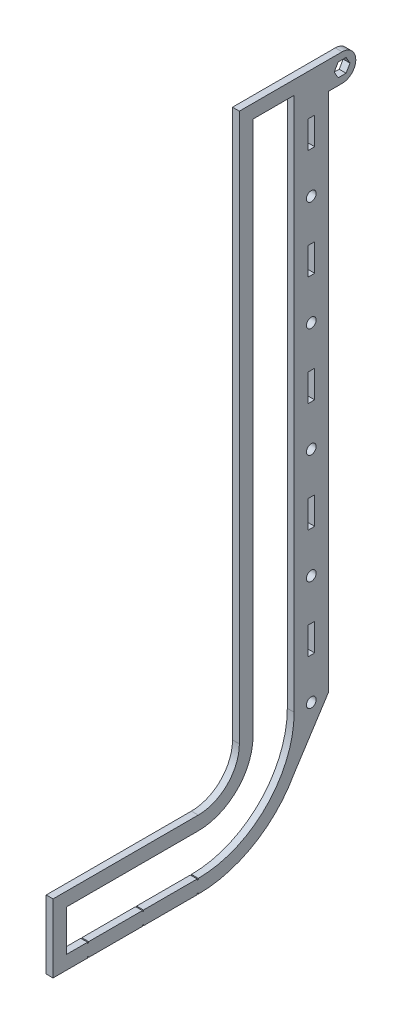
SolidWorks part; units mm, degrees
ref_plane "Front Plane" through (0, 0, 0) normal (0, 0, 1) x (1, 0, 0)
ref_plane "Top Plane" through (0, 0, 0) normal (0, 1, 0) x (1, 0, 0)
ref_plane "Right Plane" through (0, 0, 0) normal (1, 0, 0) x (0, 0, -1)
sketch "Sketch2" plane through (0, 0, 0) normal (1, 0, 0) x (0, 0, -1)
  line L0 (-44.958, -44.45) -> (-69.85, -44.45)
  line L1 (15.875, 254) -> (22.225, 254)
  line L2 (0, 0) -> (0, 247.65)
  line L3 (0, 254) -> (15.875, 254)
  line L4 (15.875, 0) -> (15.875, 241.3)
  line L6 (-44.958, -50.8) -> (-69.85, -50.8)
  line L7 (-111.76, -50.8) -> (-111.76, -44.45)
  line L8 (-105.41, -44.45) -> (-95.758, -44.45)
  line L9 (-44.45, -44.45) -> (-44.45, -44.958)
  line L10 (0, 254) -> (-25.4, 254)
  line L11 (-44.45, -44.958) -> (-44.958, -44.958)
  line L12 (0, 247.65) -> (-19.05, 247.65)
  line L13 (-25.4, 254) -> (-25.4, 247.65)
  line L14 (-44.958, -44.45) -> (-44.958, -44.958)
  line L15 (-25.4, 247.65) -> (-25.4, 0)
  line L16 (15.875, 241.3) -> (22.225, 241.3)
  line L17 (-19.05, 247.65) -> (-19.05, 0)
  line L18 (-44.45, -19.05) -> (-111.76, -19.05)
  line L19 (-44.45, -50.8) -> (-44.45, -50.292)
  line L20 (-44.45, -25.4) -> (-105.41, -25.4)
  line L21 (-111.76, -19.05) -> (-111.76, -25.4)
  line L22 (-44.45, -50.292) -> (-44.958, -50.292)
  line L23 (-111.76, -25.4) -> (-111.76, -44.45)
  line L24 (-44.958, -50.8) -> (-44.958, -50.292)
  line L25 (-105.41, -25.4) -> (-105.41, -44.45)
  line L26 (-70.358, -44.45) -> (-95.25, -44.45)
  line L27 (6.35, 222.25) -> (9.525, 222.25)
  line L28 (6.35, 222.25) -> (6.35, 234.95)
  line L29 (6.35, 234.95) -> (9.525, 234.95)
  line L30 (9.525, 234.95) -> (9.525, 222.25)
  line L31 (15.875, 0) -> (0, -24.5934)
  line L32 (-70.358, -50.8) -> (-95.25, -50.8)
  line L33 (-69.85, -44.45) -> (-69.85, -44.958)
  line L34 (-69.85, -44.958) -> (-70.358, -44.958)
  line L35 (9.525, 171.45) -> (9.525, 184.15)
  line L36 (6.35, 171.45) -> (9.525, 171.45)
  line L37 (6.35, 184.15) -> (6.35, 171.45)
  line L38 (6.35, 184.15) -> (9.525, 184.15)
  line L39 (9.525, 69.85) -> (9.525, 82.55)
  line L40 (6.35, 69.85) -> (9.525, 69.85)
  line L41 (6.35, 82.55) -> (6.35, 69.85)
  line L42 (6.35, 82.55) -> (9.525, 82.55)
  line L43 (6.35, 120.65) -> (9.525, 120.65)
  line L44 (6.35, 120.65) -> (6.35, 133.35)
  line L45 (6.35, 133.35) -> (9.525, 133.35)
  line L46 (9.525, 133.35) -> (9.525, 120.65)
  line L47 (6.35, 19.05) -> (9.525, 19.05)
  line L48 (6.35, 19.05) -> (6.35, 31.75)
  line L49 (6.35, 31.75) -> (9.525, 31.75)
  line L50 (9.525, 31.75) -> (9.525, 19.05)
  line L51 (-70.358, -44.45) -> (-70.358, -44.958)
  line L52 (-95.758, -50.8) -> (-111.76, -50.8)
  line L53 (-95.25, -44.45) -> (-95.25, -44.958)
  line L54 (-95.25, -44.958) -> (-95.758, -44.958)
  line L55 (-95.758, -44.45) -> (-95.758, -44.958)
  line L57 (-69.85, -50.8) -> (-69.85, -50.292)
  line L58 (-69.85, -50.292) -> (-70.358, -50.292)
  line L59 (-70.358, -50.8) -> (-70.358, -50.292)
  line L61 (-95.758, -50.8) -> (-95.758, -50.292)
  line L62 (-95.758, -50.292) -> (-95.25, -50.292)
  line L63 (-95.25, -50.8) -> (-95.25, -50.292)
  line L64 (25.8826, 247.65) -> (24.0538, 250.825)
  line L65 (24.0538, 250.825) -> (20.3962, 250.825)
  line L67 (20.3962, 250.825) -> (18.5674, 247.65)
  line L68 (18.5674, 247.65) -> (20.3962, 244.5056)
  line L69 (24.0538, 244.5056) -> (20.3962, 244.5056)
  line L70 (24.0538, 244.5056) -> (25.8826, 247.65)
  circle A0 centre (7.9375, 0) radius 2.2606
  arc A1 (0, -24.5934) -> (-44.45, -50.8) centre (-44.45, 0) cw
  arc A2 (0, 0) -> (-44.45, -44.45) centre (-44.45, 0) cw
  arc A3 (-25.4, 0) -> (-44.45, -19.05) centre (-44.45, 0) cw
  arc A4 (-19.05, 0) -> (-44.45, -25.4) centre (-44.45, 0) cw
  circle A5 centre (7.9375, 50.8) radius 2.2606
  arc A6 (22.225, 254) -> (22.225, 241.3) centre (22.225, 247.65) cw
  circle A7 centre (7.9375, 101.6) radius 2.2606
  circle A9 centre (7.9375, 152.4) radius 2.2606
  circle A10 centre (7.9375, 203.2) radius 2.2606
  point P8 (0, 0)
  point P42 (7.9375, 228.6)
  point P45 (6.35, 228.6)
  point P50 (0, 0)
  point P57 (6.35, 177.8)
  point P62 (6.35, 76.2)
  point P67 (6.35, 127)
  point P72 (6.35, 25.4)
  point P86 (0, 0)
  point P90 (22.225, 250.825)
  point P93 (19.05, 254)
  point P96 (22.225, 247.65)
  point P97 (0, 0)
  point P98 (0, 0)
  point P99 (0, 0)
extrude "Boss-Extrude1" add sketch "Sketch2" along normal blind 3.175
